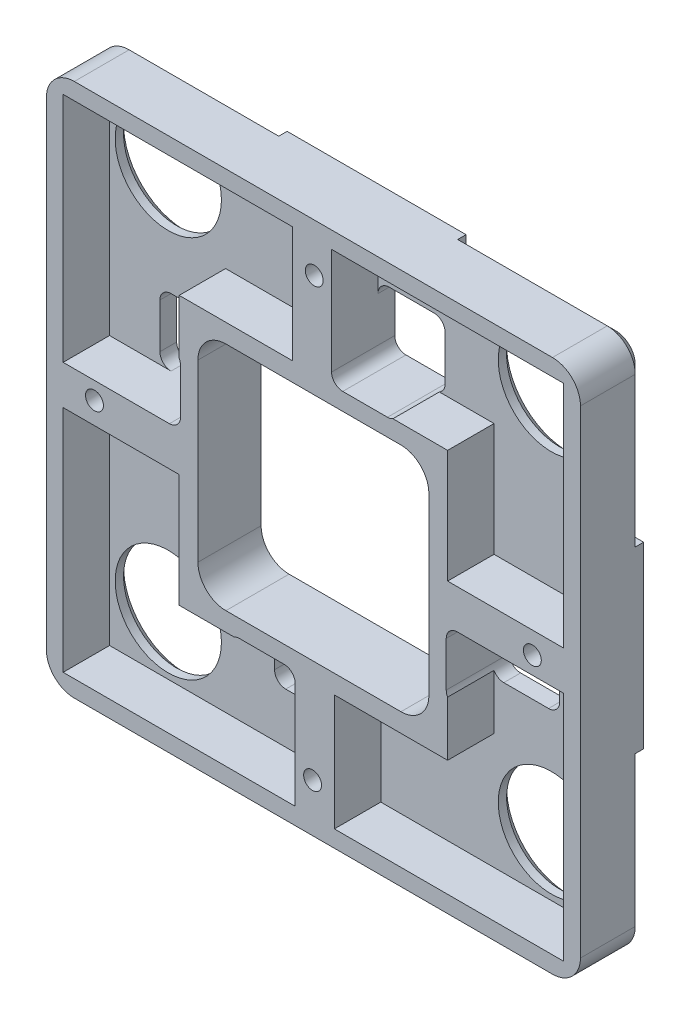
SolidWorks part; units mm, degrees
ref_plane "Front" through (0, 0, 0) normal (0, 0, 1) x (1, 0, 0)
ref_plane "Top" through (0, 0, 0) normal (0, 1, 0) x (1, 0, 0)
ref_plane "Right" through (0, 0, 0) normal (1, 0, 0) x (0, 0, -1)
sketch "ｽｹｯﾁ1" plane through (0, 0, 0) normal (0, 0, 1) x (1, 0, 0)
  line L1 (47.75, -47.75) -> (-47.75, -47.75)
  line L2 (47.75, -47.75) -> (47.75, 47.75)
  line L3 (47.75, 47.75) -> (-47.75, 47.75)
  line L4 (-47.75, -47.75) -> (-47.75, 47.75)
  line L5 (47.75, -47.75) -> (-47.75, 47.75) construction
  line L6 (47.75, 47.75) -> (-47.75, -47.75) construction
  circle A0 centre (-34.25, 34.25) radius 9.5
  circle A1 centre (34.25, 34.25) radius 9.5
  circle A2 centre (34.25, -34.25) radius 9.5
  circle A3 centre (-34.25, -34.25) radius 9.5
  point P0 (0, 0)
  dimension "D10" = 19
  dimension "D1" = 95.5
  dimension "D2" = 13.5
  dimension "D3" = 13.5
  dimension "D4" = 13.5
  dimension "D5" = 13.5
  dimension "D6" = 13.5
  dimension "D7" = 13.5
  dimension "D8" = 13.5
  dimension "D9" = 13.5
extrude "ﾎﾞｽ - 押し出し1" add sketch "ｽｹｯﾁ1" along normal blind 3
sketch "ｽｹｯﾁ3" plane through (0, 0, 3) normal (0, 0, 1) x (1, 0, 0)
  line L1 (21, -21) -> (-21, -21)
  line L2 (21, -21) -> (21, 21)
  line L3 (21, 21) -> (-21, 21)
  line L4 (-21, -21) -> (-21, 21)
  line L5 (21, -21) -> (-21, 21) construction
  line L6 (21, 21) -> (-21, -21) construction
  point P0 (0, 0)
  dimension "D1" = 42
extrude "ｶｯﾄ - 押し出し2" cut sketch "ｽｹｯﾁ3" against normal through all
sketch "ｽｹｯﾁ5" plane through (0, 0, 3) normal (0, 0, 1) x (1, 0, 0)
  line L0 (-47.75, 47.75) -> (-47.75, -47.75) construction
  line L1 (47.75, -47.75) -> (-47.75, -47.75)
  line L2 (47.75, -47.75) -> (47.75, 47.75)
  line L3 (47.75, 47.75) -> (-47.75, 47.75)
  line L4 (-47.75, -47.75) -> (-47.75, 47.75)
  line L5 (47.75, -47.75) -> (-47.75, 47.75) construction
  line L6 (47.75, 47.75) -> (-47.75, -47.75) construction
  line L8 (44.75, -44.75) -> (-44.75, -44.75)
  line L9 (44.75, -44.75) -> (44.75, 44.75)
  line L10 (44.75, 44.75) -> (-44.75, 44.75)
  line L11 (-44.75, -44.75) -> (-44.75, 44.75)
  line L12 (44.75, -44.75) -> (-44.75, 44.75) construction
  line L13 (44.75, 44.75) -> (-44.75, -44.75) construction
  point P0 (0, 0)
  point P8 (0, 0)
  dimension "D1" = 3
extrude "ﾎﾞｽ - 押し出し2" add sketch "ｽｹｯﾁ5" along normal blind 8.3
fillet "ﾌｨﾚｯﾄ1" radius 5 4 edges at (47.75, -47.75, 5.65) (-47.75, -47.75, 5.65) (47.75, 47.75, 5.65) (-47.75, 47.75, 5.65)
sketch "ｽｹｯﾁ7" plane through (0, 0, 3) normal (0, 0, 1) x (1, 0, 0)
  line L0 (21, 21) -> (-21, 21) construction
  line L1 (21, -21) -> (-21, -21)
  line L2 (21, -21) -> (21, 21)
  line L3 (21, 21) -> (-21, 21)
  line L4 (-21, -21) -> (-21, 21)
  line L5 (21, -21) -> (-21, 21) construction
  line L6 (21, 21) -> (-21, -21) construction
  line L8 (24, -24) -> (-24, -24)
  line L9 (24, -24) -> (24, 24)
  line L10 (24, 24) -> (-24, 24)
  line L11 (-24, -24) -> (-24, 24)
  line L12 (24, -24) -> (-24, 24) construction
  line L13 (24, 24) -> (-24, -24) construction
  point P0 (0, 0)
  point P8 (0, 0)
  dimension "D1" = 3
extrude "ﾎﾞｽ - 押し出し4" add sketch "ｽｹｯﾁ7" along normal up to surface (8.3 mm away) up to face at (0, 0, 11.3)
chamfer "面取り3" distance 1.5 angle 45 8 edges at (46.2855, 46.2855, 0) (0, 47.75, 0) (-46.2855, 46.2855, 0) (-47.75, 0, 0) (-46.2855, -46.2855, 0) (0, -47.75, 0) (46.2855, -46.2855, 0) (47.75, 0, 0)
chamfer "面取り5" distance 1.5 angle 45 4 edges at (-24.75, -34.25, 0) (-24.75, 34.25, 0) (43.75, 34.25, 0) (43.75, -34.25, 0)
sketch "ｽｹｯﾁ12" plane through (0, 0, 0) normal (0, 0, -1) x (-1, 0, 0)
  circle A0 centre (-0.15, 39.15) radius 1.6
  circle A1 centre (-39.15, -0.15) radius 1.6
  circle A2 centre (39.15, 0.15) radius 1.6
  circle A3 centre (0.15, -39.15) radius 1.6
  dimension "D5" = 3.2
extrude "ｶｯﾄ - 押し出し8" cut sketch "ｽｹｯﾁ12" against normal through all
sketch "ｽｹｯﾁ13" plane through (0, 0, 3) normal (0, 0, 1) x (1, 0, 0)
  line L0 (-44.75, 44.75) -> (-44.75, -44.75) construction
  line L1 (-44.75, 3.25) -> (-24, 3.25)
  line L2 (-44.75, 3.25) -> (-44.75, -3.75)
  line L3 (-44.75, -3.75) -> (-24, -3.75)
  line L4 (-24, 3.25) -> (-24, -3.75)
  line L6 (-24, 24) -> (-24, -24) construction
  line L7 (-44.55, -3.75) -> (-23.95, -3.75) construction
  line L8 (-24, -24) -> (24, -24) construction
  line L9 (3.75, -24) -> (-3.25, -24)
  line L10 (3.75, -24) -> (3.75, -44.75)
  line L11 (3.75, -44.75) -> (-3.25, -44.75)
  line L12 (-3.25, -24) -> (-3.25, -44.75)
  line L13 (3.75, -44.55) -> (3.75, -23.95) construction
  line L14 (-44.75, -44.75) -> (44.75, -44.75) construction
  line L16 (24, -24) -> (24, 24) construction
  line L17 (24, -3.25) -> (44.75, -3.25)
  line L18 (24, -3.25) -> (24, 3.75)
  line L19 (24, 3.75) -> (44.75, 3.75)
  line L20 (44.75, -3.25) -> (44.75, 3.75)
  line L22 (44.75, -44.75) -> (44.75, 44.75) construction
  line L23 (44.55, 3.75) -> (23.95, 3.75) construction
  line L24 (44.75, 44.75) -> (-44.75, 44.75) construction
  line L25 (3.25, 44.75) -> (-3.75, 44.75)
  line L26 (3.25, 44.75) -> (3.25, 24)
  line L27 (3.25, 24) -> (-3.75, 24)
  line L28 (-3.75, 44.75) -> (-3.75, 24)
  line L29 (-3.75, 44.55) -> (-3.75, 23.95) construction
  line L30 (24, 24) -> (-24, 24) construction
  dimension "D1" = 7
extrude "ﾎﾞｽ - 押し出し5" add sketch "ｽｹｯﾁ13" along normal up to surface (8.3 mm away) up to face at (0, 0, 11.3)
sketch "ｽｹｯﾁ14" plane through (0, 0, 11.3) normal (0, 0, 1) x (1, 0, 0)
  circle A0 centre (-39.15, 0.15) radius 1.6
  circle A1 centre (-0.15, -39.15) radius 1.6
  circle A2 centre (39.15, -0.15) radius 1.6
  circle A3 centre (0.15, 39.15) radius 1.6
  dimension "D1" = 3.2
extrude "ｶｯﾄ - 押し出し9" cut sketch "ｽｹｯﾁ14" against normal through all
sketch "ｽｹｯﾁ15" plane through (0, 0, 0) normal (0, 0, -1) x (-1, 0, 0)
  line L0 (42.75, 46.25) -> (-42.75, 46.25) construction
  line L1 (-16, 46.25) -> (16, 46.25)
  line L2 (-16, 46.25) -> (-16, 47.75)
  line L3 (-16, 47.75) -> (16, 47.75)
  line L4 (16, 46.25) -> (16, 47.75)
  line L5 (-42.75, 47.75) -> (42.75, 47.75) construction
  line L6 (46.25, -42.75) -> (46.25, 42.75) construction
  line L7 (46.25, 16) -> (47.75, 16)
  line L8 (46.25, 16) -> (46.25, -16)
  line L9 (46.25, -16) -> (47.75, -16)
  line L10 (47.75, 16) -> (47.75, -16)
  line L11 (47.75, 42.75) -> (47.75, -42.75) construction
  line L12 (-42.75, -46.25) -> (42.75, -46.25) construction
  line L13 (16, -46.25) -> (-16, -46.25)
  line L14 (16, -46.25) -> (16, -47.75)
  line L15 (16, -47.75) -> (-16, -47.75)
  line L16 (-16, -46.25) -> (-16, -47.75)
  line L17 (42.75, -47.75) -> (-42.75, -47.75) construction
  line L18 (-46.25, 42.75) -> (-46.25, -42.75) construction
  line L19 (-46.25, -16) -> (-47.75, -16)
  line L20 (-46.25, -16) -> (-46.25, 16)
  line L21 (-46.25, 16) -> (-47.75, 16)
  line L22 (-47.75, -16) -> (-47.75, 16)
  line L24 (-47.75, -42.75) -> (-47.75, 42.75) construction
  dimension "D1" = 32
  dimension "D2" = 16
  dimension "D3" = 16
extrude "ﾎﾞｽ - 押し出し6" add sketch "ｽｹｯﾁ15" against normal up to surface (11.3 mm away) up to face at (-37.55, 0.15, 11.3)
sketch "ｽｹｯﾁ16" plane through (0, 0, 3) normal (0, 0, 1) x (1, 0, 0)
  line L0 (-23.75, 5.25) -> (-23.75, -3.75) construction
  line L5 (-24, 3.25) -> (-44.75, 3.25) construction
  line L10 (5.25, 23.75) -> (-3.75, 23.75) construction
  line L15 (3.25, 24) -> (3.25, 44.75) construction
  line L20 (23.75, -5.25) -> (23.75, 3.75) construction
  line L25 (24, -3.25) -> (44.75, -3.25) construction
  line L26 (-5.25, -23.75) -> (3.75, -23.75) construction
  line L27 (3.25, 23.75) -> (15.25, 23.75)
  line L28 (3.25, 23.75) -> (3.25, 35.75)
  line L29 (3.25, 35.75) -> (15.25, 35.75)
  line L30 (15.25, 23.75) -> (15.25, 35.75)
  line L32 (3.25, 44.75) -> (3.25, 33.75) construction
  line L34 (23.75, -3.25) -> (35.75, -3.25)
  line L35 (23.75, -3.25) -> (23.75, -15.25)
  line L36 (23.75, -15.25) -> (35.75, -15.25)
  line L37 (35.75, -3.25) -> (35.75, -15.25)
  line L41 (-3.25, -23.75) -> (-15.25, -23.75)
  line L42 (-3.25, -23.75) -> (-3.25, -35.75)
  line L43 (-3.25, -35.75) -> (-15.25, -35.75)
  line L44 (-15.25, -23.75) -> (-15.25, -35.75)
  line L45 (-15.25, -33.75) -> (-15.25, -25.75) construction
  line L46 (-3.25, -25.75) -> (-3.25, -33.75) construction
  line L48 (-23.75, 3.25) -> (-35.75, 3.25)
  line L49 (-23.75, 3.25) -> (-23.75, 15.25)
  line L50 (-23.75, 15.25) -> (-35.75, 15.25)
  line L51 (-35.75, 3.25) -> (-35.75, 15.25)
  dimension "D1" = 12
  dimension "D2" = 12
  dimension "D3" = 12
extrude "ｶｯﾄ - 押し出し10" cut sketch "ｽｹｯﾁ16" against normal through all and the other way through all
sketch "ｽｹｯﾁ17" plane through (0, 0, 0) normal (0, 0, -1) x (-1, 0, 0)
  line L1 (-21, 21) -> (21, 21)
  line L2 (-21, 21) -> (-21, -21)
  line L3 (-21, -21) -> (21, -21)
  line L4 (21, 21) -> (21, -21)
extrude "ﾎﾞｽ - 押し出し7" add sketch "ｽｹｯﾁ17" against normal through all
fillet "ﾌｨﾚｯﾄ2" radius 2 16 edges at (3.25, 35.75, 1.5) (15.25, 35.75, 1.5) (15.25, 23.75, 5.65) (3.25, 23.75, 5.65) (-35.75, 15.25, 1.5) (-35.75, 3.25, 1.5) (-23.75, 3.25, 5.65) (-23.75, 15.25, 5.65) (-15.25, -23.75, 5.65) (-3.25, -23.75, 5.65) (-3.25, -35.75, 1.5) (-15.25, -35.75, 1.5) (23.75, -15.25, 5.65) (35.75, -15.25, 1.5) (35.75, -3.25, 1.5) (23.75, -3.25, 5.65)
sketch "ｽｹｯﾁ18" plane through (0, 0, 0) normal (0, 0, -1) x (-1, 0, 0)
  line L1 (-20.65, 20.65) -> (20.65, 20.65)
  line L2 (-20.65, 20.65) -> (-20.65, -20.65)
  line L3 (-20.65, -20.65) -> (20.65, -20.65)
  line L4 (20.65, 20.65) -> (20.65, -20.65)
  line L5 (-20.65, 20.65) -> (20.65, -20.65) construction
  line L6 (-20.65, -20.65) -> (20.65, 20.65) construction
  point P0 (0, 0)
  dimension "D1" = 41.3
extrude "ｶｯﾄ - 押し出し11" cut sketch "ｽｹｯﾁ18" against normal through all
fillet "ﾌｨﾚｯﾄ3" radius 5 4 edges at (20.65, -20.65, 5.65) (-20.65, -20.65, 5.65) (-20.65, 20.65, 5.65) (20.65, 20.65, 5.65)
equation "\"A\"= 13.5"
equation "\"B\"= 13.5"
equation "\"D2@ｽｹｯﾁ1\"=\"A\""
equation "\"D3@ｽｹｯﾁ1\"=\"A\""
equation "\"D4@ｽｹｯﾁ1\"=\"A\""
equation "\"D5@ｽｹｯﾁ1\"=\"A\""
equation "\"D9@ｽｹｯﾁ1\"=\"A\""
